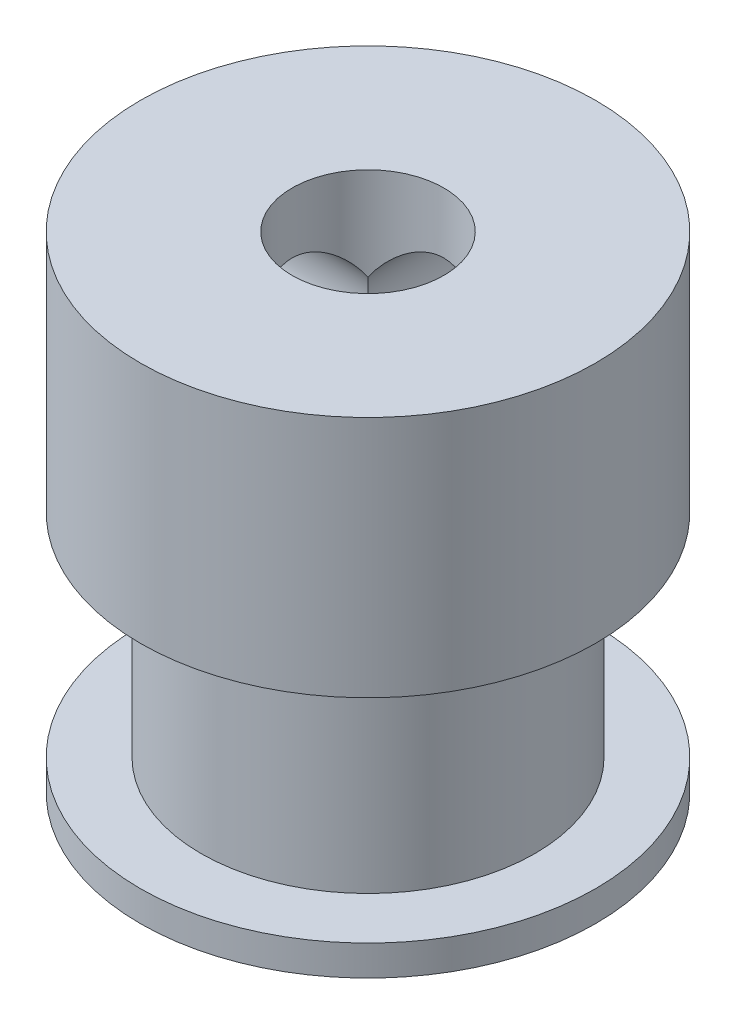
SolidWorks part; units mm, degrees
ref_plane "Plan de face" through (0, 0, 0) normal (0, 0, 1) x (1, 0, 0)
ref_plane "Plan de dessus" through (0, 0, 0) normal (0, 1, 0) x (1, 0, 0)
ref_plane "Plan de droite" through (0, 0, 0) normal (1, 0, 0) x (0, 0, -1)
sketch "Esquisse1" plane through (0, 0, 0) normal (0, 1, 0) x (1, 0, 0)
  circle A0 centre (0, 0) radius 7.5
  dimension "D1" = 15
extrude "Boss.-Extru.1" add sketch "Esquisse1" along normal blind 16
sketch "Esquisse2" plane through (0, 0, 0) normal (1, 0, 0) x (0, 0, -1)
  line L0 (-7.5, 16) -> (-7.5, 0) construction
  line L1 (-7.5, 8) -> (-5.5, 8)
  line L2 (-7.5, 8) -> (-7.5, 1)
  line L3 (-7.5, 1) -> (-5.5, 1)
  line L4 (-5.5, 8) -> (-5.5, 1)
  line L6 (-7.5, 0) -> (7.5, 0) construction
  line L7 (0, 0) -> (0, 18.3319) construction
  dimension "D1" = 7
  dimension "D2" = 1
  dimension "D3" = 2
revolve "Enlèvement de matière-Révolution1" cut sketch "Esquisse2" angle 360 about L7
sketch "Esquisse3" plane through (0, 16, 0) normal (0, 1, 0) x (1, 0, 0)
  circle A0 centre (0, 0) radius 2.5
  dimension "D1" = 5
extrude "Enlèv. mat.-Extru.1" cut sketch "Esquisse3" against normal blind 16
sketch "Esquisse4" plane through (0, 0, 0) normal (0, 0, 1) x (1, 0, 0)
  line L0 (7.5, 16) -> (-7.5, 16) construction
  circle A0 centre (0, 12) radius 2
  dimension "D1" = 4
  dimension "D2" = 4
extrude "Enlèv. mat.-Extru.2" cut sketch "Esquisse4" against normal through all
pattern_circular "Répétition circulaire1" count 2 over 90 about axis through (0, 16, 0) along (0, -1, 0) of "Enlèv. mat.-Extru.2"
